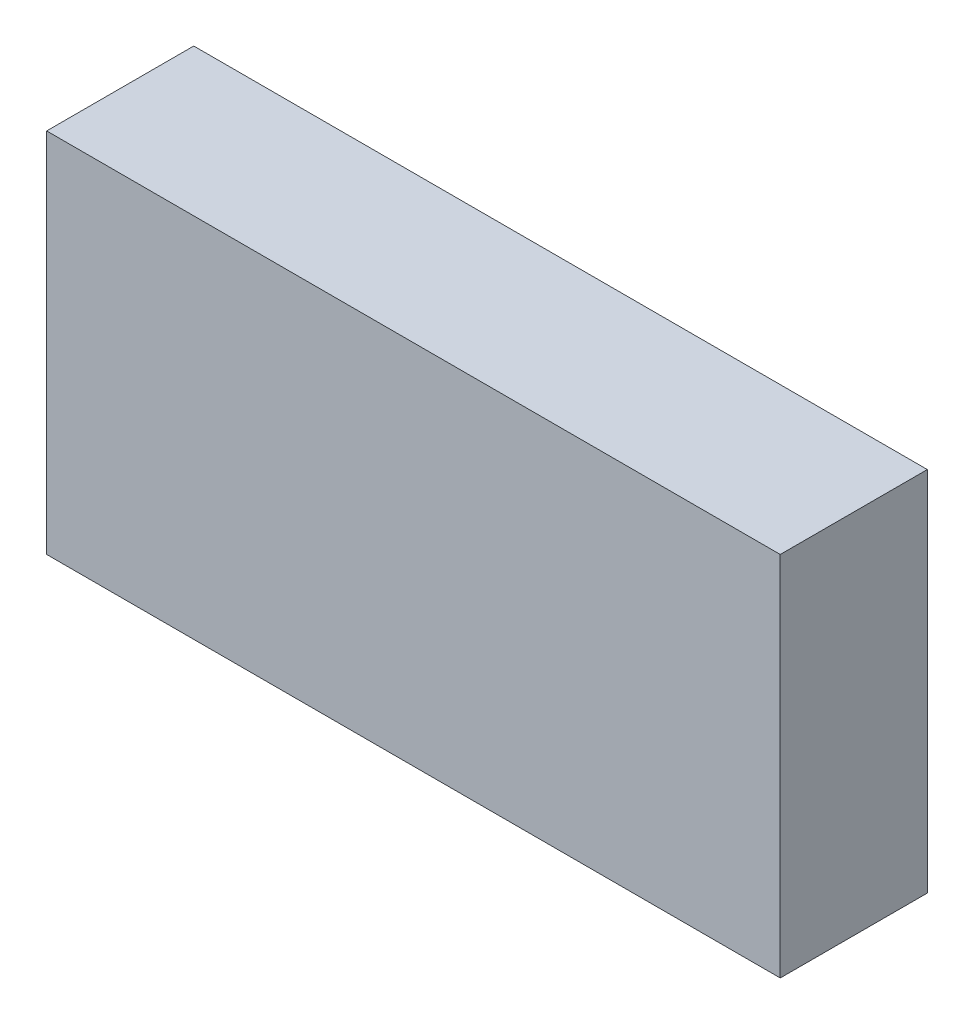
SolidWorks part; units mm, degrees
ref_plane "Front Plane" through (0, 0, 0) normal (0, 0, 1) x (1, 0, 0)
ref_plane "Top Plane" through (0, 0, 0) normal (0, 1, 0) x (1, 0, 0)
ref_plane "Right Plane" through (0, 0, 0) normal (1, 0, 0) x (0, 0, -1)
sketch "Sketch1" plane through (0, 0, 0) normal (0, 1, 0) x (1, 0, 0)
  line L1 (0, 0) -> (100.076, 0)
  line L2 (0, 0) -> (0, 20.066)
  line L3 (0, 20.066) -> (100.076, 20.066)
  line L4 (100.076, 0) -> (100.076, 20.066)
  dimension "D1" = 100.076
  dimension "D2" = 20.066
extrude "Boss-Extrude1" add sketch "Sketch1" along normal blind 50.038
